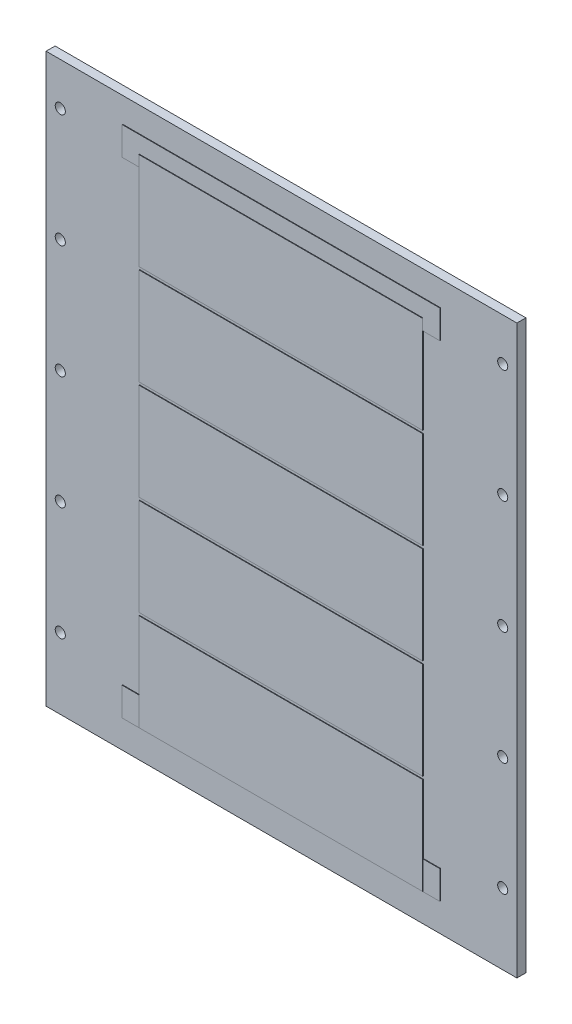
SolidWorks part; units mm, degrees
ref_plane "Front Plane" through (0, 0, 0) normal (0, 0, 1) x (1, 0, 0)
ref_plane "Top Plane" through (0, 0, 0) normal (0, 1, 0) x (1, 0, 0)
ref_plane "Right Plane" through (0, 0, 0) normal (1, 0, 0) x (0, 0, -1)
sketch "Sketch1" plane through (0, 0, 0) normal (0, 0, 1) x (1, 0, 0)
  line L1 (-41.5, -50) -> (41.5, -50)
  line L2 (-41.5, -50) -> (-41.5, 50)
  line L3 (-41.5, 50) -> (41.5, 50)
  line L4 (41.5, -50) -> (41.5, 50)
  line L5 (-41.5, -50) -> (41.5, 50) construction
  line L6 (-41.5, 50) -> (41.5, -50) construction
  point P0 (0, 0)
  dimension "D1" = 83
  dimension "D2" = 100
extrude "Boss-Extrude1" add sketch "Sketch1" along normal blind 1.5875
sketch "Sketch2" plane through (0, 0, 1.5875) normal (0, 0, 1) x (1, 0, 0)
  line L0 (-35, 45) -> (35, 45)
  line L1 (35, 45) -> (37.5, 42.5)
  line L2 (37.5, 42.5) -> (37.5, 30.5)
  line L3 (35, 28) -> (-35, 28)
  line L4 (-37.5, 30.5) -> (-37.5, 42.5)
  line L5 (-37.5, 42.5) -> (-35, 45)
  line L6 (0, 0) -> (0, 50) construction
  line L7 (41.5, 50) -> (-41.5, 50) construction
  line L8 (-35, 28) -> (-37.5, 30.5)
  line L9 (37.5, 30.5) -> (35, 28)
  line L10 (-35, 26.75) -> (35, 26.75)
  line L11 (35, 26.75) -> (37.5, 24.25)
  line L12 (37.5, 24.25) -> (37.5, 12.25)
  line L13 (35, 9.75) -> (-35, 9.75)
  line L14 (-37.5, 12.25) -> (-37.5, 24.25)
  line L15 (-37.5, 24.25) -> (-35, 26.75)
  line L16 (-35, 9.75) -> (-37.5, 12.25)
  line L17 (37.5, 12.25) -> (35, 9.75)
  line L18 (-35, 8.5) -> (35, 8.5)
  line L19 (35, 8.5) -> (37.5, 6)
  line L20 (37.5, 6) -> (37.5, -6)
  line L21 (35, -8.5) -> (-35, -8.5)
  line L22 (-37.5, -6) -> (-37.5, 6)
  line L23 (-37.5, 6) -> (-35, 8.5)
  line L24 (-35, -8.5) -> (-37.5, -6)
  line L25 (37.5, -6) -> (35, -8.5)
  line L26 (-35, -9.75) -> (35, -9.75)
  line L27 (35, -9.75) -> (37.5, -12.25)
  line L28 (37.5, -12.25) -> (37.5, -24.25)
  line L29 (35, -26.75) -> (-35, -26.75)
  line L30 (-37.5, -24.25) -> (-37.5, -12.25)
  line L31 (-37.5, -12.25) -> (-35, -9.75)
  line L32 (-35, -26.75) -> (-37.5, -24.25)
  line L33 (37.5, -24.25) -> (35, -26.75)
  line L34 (-35, -28) -> (35, -28)
  line L35 (35, -28) -> (37.5, -30.5)
  line L36 (37.5, -30.5) -> (37.5, -42.5)
  line L37 (35, -45) -> (-35, -45)
  line L38 (-37.5, -42.5) -> (-37.5, -30.5)
  line L39 (-37.5, -30.5) -> (-35, -28)
  line L40 (-35, -45) -> (-37.5, -42.5)
  line L41 (37.5, -42.5) -> (35, -45)
  line L42 (-41.5, -50) -> (41.5, -50) construction
  point P4 (37.5, 28)
  point P5 (-37.5, 28)
  point P20 (37.5, 9.75)
  point P21 (-37.5, 9.75)
  point P30 (37.5, -8.5)
  point P31 (-37.5, -8.5)
  point P40 (37.5, -26.75)
  point P41 (-37.5, -26.75)
  point P50 (37.5, -45)
  point P51 (-37.5, -45)
  dimension "D1" = 75
  dimension "D2" = 2.5
  dimension "D3" = 45
  dimension "D4" = 17
  dimension "D5" = 5
  dimension "D7" = 5
  dimension "D6" = 5
extrude "Boss-Extrude2" [suppressed] add sketch "Sketch2" along normal blind 0.25
hole_wizard "#0 Clearance Hole1" positions "Sketch4" profile "Sketch3" hole size "#0" standard "ANSI Inch"
sketch "Sketch4" plane through (0, 0, 1.5875) normal (0, 0, 1) x (1, 0, 0)
  line L0 (-41.5, 50) -> (-41.5, -50) construction
  line L1 (41.5, 50) -> (-41.5, 50) construction
  line L2 (-41.5, -50) -> (41.5, -50) construction
  line L3 (0, 50) -> (0, -50) construction
  point P56 (-39, 42.5)
  point P79 (-39, 22.5)
  point P80 (-39, 2.5)
  point P81 (-39, -17.5)
  point P82 (-39, -37.5)
  point P92 (39, -37.5)
  point P93 (39, -17.5)
  point P94 (39, 2.5)
  point P95 (39, 22.5)
  point P96 (39, 42.5)
  dimension "D1" = 2.5
  dimension "D2" = 7.5
  dimension "D3" = 5
  dimension "D4" = 20
sketch "Sketch3" plane through (-39, 42.5, 1.5875) normal (1, 0, 0) x (0, -1, 0)
  line L0 (0, 0) -> (0, 3.7092)
  line L1 (0, 3.7092) -> (0.889, 3.175)
  line L2 (0.889, 3.175) -> (0.889, 0)
  line L5 (0.889, 0) -> (0, 0)
  line L10 (0, 3.7092) -> (-0.889, 3.175) construction
  line L11 (0, -6.35) -> (0, 107.95) construction
  dimension "Hole Dia." = 1.778
  dimension "Hole Depth" = 3.175
  dimension "Drill Angle" = 118
sketch "Sketch5" plane through (0, 0, 1.5875) normal (0, 0, 1) x (1, 0, 0)
  line L0 (-25, 24.9) -> (25, 24.9)
  line L1 (-25, 42.5) -> (25, 42.5)
  line L2 (-25, 42.5) -> (-25, 25.4)
  line L3 (-25, 25.4) -> (25, 25.4)
  line L4 (25, 42.5) -> (25, 25.4)
  line L5 (-25, 24.9) -> (-25, 7.8)
  line L6 (-25, 7.8) -> (25, 7.8)
  line L7 (25, 24.9) -> (25, 7.8)
  line L8 (-25, 7.3) -> (25, 7.3)
  line L9 (-25, 7.3) -> (-25, -9.8)
  line L10 (-25, -9.8) -> (25, -9.8)
  line L11 (25, 7.3) -> (25, -9.8)
  line L12 (-25, -10.3) -> (25, -10.3)
  line L13 (-25, -10.3) -> (-25, -27.4)
  line L14 (-25, -27.4) -> (25, -27.4)
  line L15 (25, -10.3) -> (25, -27.4)
  line L17 (-25, -27.9) -> (25, -27.9)
  line L18 (-25, -27.9) -> (-25, -45)
  line L19 (-25, -45) -> (25, -45)
  line L20 (25, -27.9) -> (25, -45)
  line L21 (-41.5, -50) -> (41.5, -50) construction
  line L22 (0, 0) -> (0, -9.8) construction
  dimension "D1" = 87.5
  dimension "D2" = 50
  dimension "D4" = 0.5
  dimension "D5" = 5
  dimension "D3" = 5
extrude "Boss-Extrude3" add sketch "Sketch5" along normal blind 0.1
sketch "Sketch6" plane through (0, 0, 1.5875) normal (0, 0, 1) x (1, 0, 0)
  line L0 (25, 42.5) -> (-25, 42.5) construction
  line L1 (-25, 42.6) -> (25, 42.6)
  line L2 (-28, 42.6) -> (-28, 45.6)
  line L3 (-28, 45.6) -> (28, 45.6)
  line L4 (28, 42.6) -> (28, 45.6)
  line L6 (25, 25.4) -> (25, 42.5) construction
  line L7 (-25, 42.5) -> (-25, 25.4) construction
  line L9 (-28, 42.6) -> (-28, 40.6)
  line L10 (-28, 40.6) -> (-25, 40.6)
  line L11 (-25, 42.6) -> (-25, 40.6)
  line L12 (25, 25.4) -> (25, 42.5) construction
  line L14 (28, 42.6) -> (28, 40.6)
  line L15 (28, 40.6) -> (25, 40.6)
  line L16 (25, 42.6) -> (25, 40.6)
  dimension "D1" = 3
  dimension "D2" = 56
  dimension "D3" = 0.1
  dimension "D4" = 3
  dimension "D5" = 2
  dimension "D6" = 2
extrude "Boss-Extrude4" add sketch "Sketch6" along normal blind 0.1 separate body
sketch "Sketch7" plane through (0, 0, 1.5875) normal (0, 0, 1) x (1, 0, 0)
  line L0 (28, 40.6) -> (28, 45.6) construction
  line L1 (25.01, -45) -> (28, -45)
  line L2 (25.01, -45) -> (25.01, -40)
  line L3 (25.01, -40) -> (28, -40)
  line L4 (28, -45) -> (28, -40)
  line L5 (25, -45) -> (25, -27.9) construction
  line L6 (-25, -45) -> (25, -45) construction
  line L7 (0, 0) -> (0, -21.944) construction
  line L8 (-28, -45) -> (-28, -40)
  line L9 (-25.01, -40) -> (-28, -40)
  line L10 (-25.01, -45) -> (-25.01, -40)
  line L11 (-25.01, -45) -> (-28, -45)
  dimension "D1" = 0.01
extrude "Boss-Extrude5" add sketch "Sketch7" along normal blind 0.1
